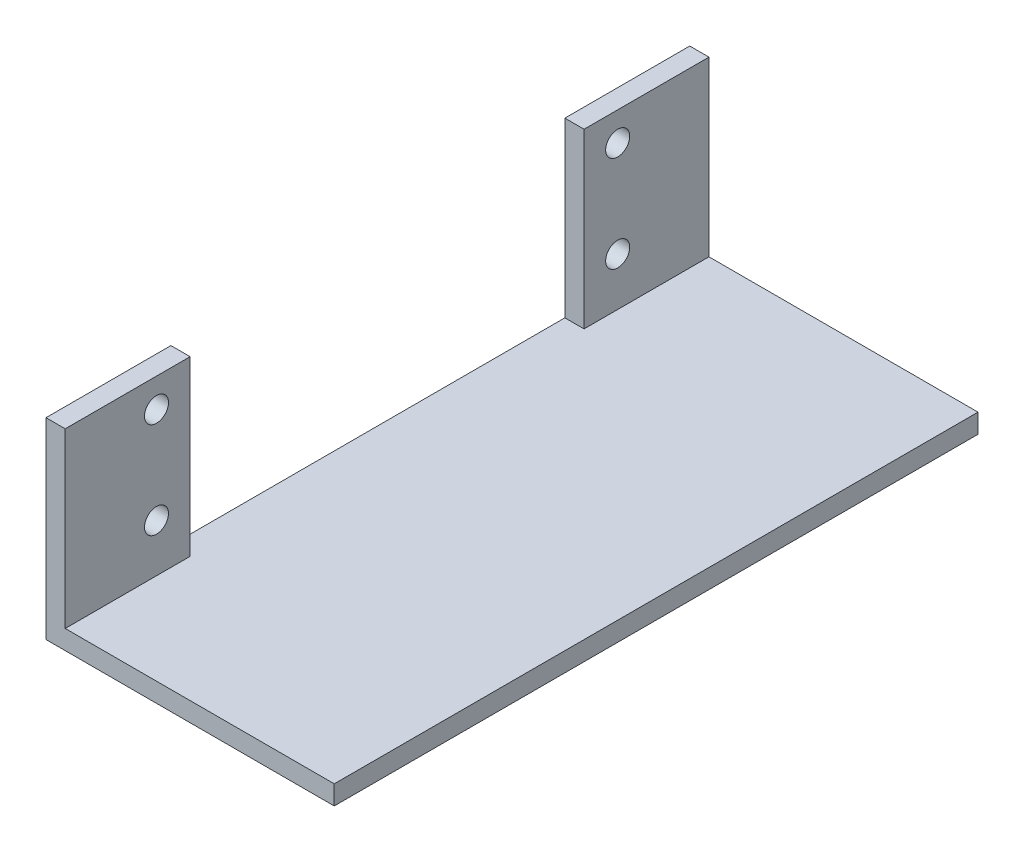
SolidWorks part; units mm, degrees
ref_plane "Front" through (0, 0, 0) normal (0, 0, 1) x (1, 0, 0)
ref_plane "Top" through (0, 0, 0) normal (0, 1, 0) x (1, 0, 0)
ref_plane "Right" through (0, 0, 0) normal (1, 0, 0) x (0, 0, -1)
sketch "Esquisse1" plane through (0, 0, 0) normal (0, 0, 1) x (1, 0, 0)
  line L0 (0, 20) -> (0, 0)
  line L1 (0, 0) -> (30, 0)
  dimension "D1" = 20
  dimension "D2" = 30
extrude "Extru.-Mince1" add sketch "Esquisse1" along normal mid plane 67 thin thin type one direction reverse wall 2
sketch "Esquisse2" plane through (0, 0, 0) normal (-1, 0, 0) x (0, 0, 1)
  line L0 (-24, 7) -> (24, 7) construction
  line L1 (-24, 7) -> (-24, 17) construction
  line L2 (33.5, 0) -> (-33.5, 0) construction
  line L3 (33.5, 20) -> (-33.5, 20) construction
  line L4 (-20.5, 20) -> (20.5, 20)
  line L5 (-20.5, 20) -> (-20.5, 2)
  line L6 (-20.5, 2) -> (20.5, 2)
  line L7 (20.5, 20) -> (20.5, 2)
  line L8 (33.5, 2) -> (-33.5, 2) construction
  circle A0 centre (-24, 7) radius 1.25
  circle A1 centre (24, 7) radius 1.25
  circle A2 centre (24, 17) radius 1.25
  circle A3 centre (-24, 17) radius 1.25
  point P20 (0, 2)
  dimension "D6" = 2.5
  dimension "D3" = 48
  dimension "D4" = 10
  dimension "D5" = 24
  dimension "D7" = 7
  dimension "D8" = 41
  dimension "D1" = 2
  dimension "D2" = 2
extrude "Enlèv. mat.-Extru.1" cut sketch "Esquisse2" against normal up to surface (2 mm away) up to face at (2, 11, 0)
equation "\"D5@Esquisse2\"=\"D3@Esquisse2\"/2"
